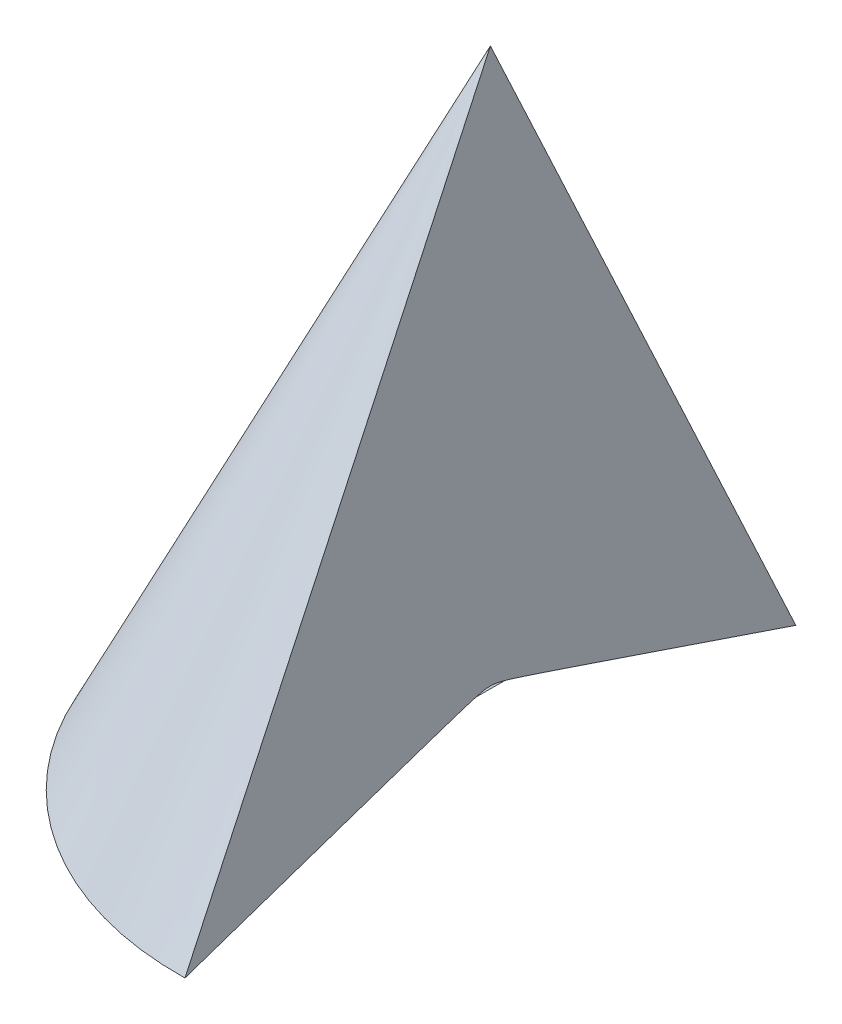
SolidWorks part; units mm, degrees
ref_plane "Front Plane" through (0, 0, 0) normal (0, 0, 1) x (1, 0, 0)
ref_plane "Top Plane" through (0, 0, 0) normal (0, 1, 0) x (1, 0, 0)
ref_plane "Right Plane" through (0, 0, 0) normal (1, 0, 0) x (0, 0, -1)
sketch "Sketch1" plane through (0, 0, 0) normal (0, 0, 1) x (1, 0, 0)
  line L0 (0, 0) -> (1.8345, 100.3653) construction
  line L1 (1.8345, 100.3653) -> (-56.0557, -17.878)
  line L2 (-56.0557, -17.878) -> (0, 0)
  line L3 (0, 0) -> (1.8345, 100.3653)
revolve "Revolve2" add sketch "Sketch1" angle 360 about L0
sketch "Sketch4" plane through (0, 0, 0) normal (0, 0, 1) x (1, 0, 0)
  line L0 (1.8345, 100.3653) -> (1.8345, -33.1131)
  line L1 (1.8345, -33.1131) -> (93.2808, -23.6081)
  line L2 (93.2808, -23.6081) -> (67.9049, 121.2875)
  line L3 (67.9049, 121.2875) -> (19.6892, 148.6691)
  line L4 (19.6892, 148.6691) -> (11.9142, 134.9783)
  line L5 (1.8345, 100.3653) -> (11.9142, 134.9783)
extrude "Cut-Extrude2" cut sketch "Sketch4" against normal through all both and the other way through all
